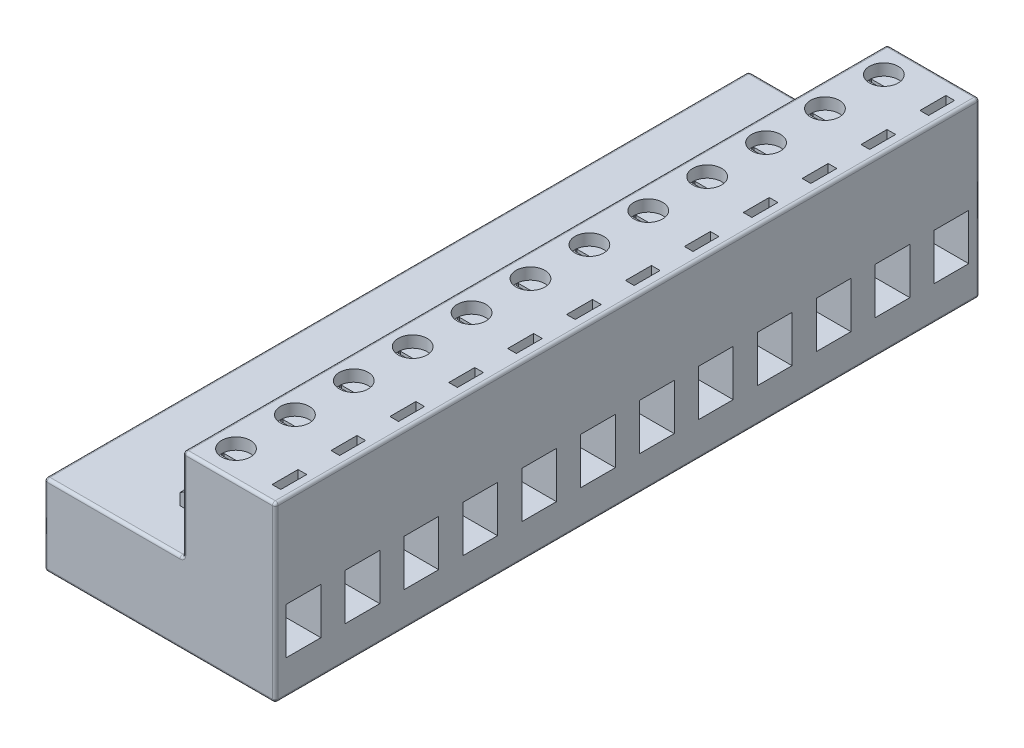
SolidWorks part; units mm, degrees
ref_plane "Front Plane" through (0, 0, 0) normal (0, 0, 1) x (1, 0, 0)
ref_plane "Top Plane" through (0, 0, 0) normal (0, 1, 0) x (1, 0, 0)
ref_plane "Right Plane" through (0, 0, 0) normal (1, 0, 0) x (0, 0, -1)
sketch "Sketch1" plane through (0, 0, 0) normal (0, 0, 1) x (1, 0, 0)
  line L0 (-4, -0.5) -> (-16, -0.5)
  line L1 (-4, -7.5) -> (4, -7.5)
  line L2 (-4, -7.5) -> (-4, 7.5)
  line L3 (-4, 7.5) -> (4, 7.5)
  line L4 (4, -7.5) -> (4, 7.5)
  line L5 (-4, -7.5) -> (4, 7.5) construction
  line L6 (-4, 7.5) -> (4, -7.5) construction
  line L7 (-16, -0.5) -> (-16, -7.5)
  line L8 (-16, -7.5) -> (-4, -7.5)
  point P0 (0, 0)
  dimension "D1" = 20
  dimension "D2" = 8
  dimension "D3" = 7
  dimension "D4" = 15
extrude "Boss-Extrude1" add sketch "Sketch1" along normal mid plane 61 contours L1 L4 L3 L2 | L7 L8 L2 L0
sketch "Sketch2" plane through (4, 0, 0) normal (1, 0, 0) x (0, 0, -1)
  line L0 (-30.5, -7.5) -> (30.5, -7.5) construction
  line L1 (-29.55, -0.5) -> (-26.55, -0.5)
  line L2 (-29.55, -0.5) -> (-29.55, -4.5)
  line L3 (-29.55, -4.5) -> (-26.55, -4.5)
  line L4 (-26.55, -0.5) -> (-26.55, -4.5)
  line L5 (-30.5, -7.5) -> (-30.5, 7.5) construction
  line L6 (-24.45, -0.5) -> (-24.45, -4.5)
  line L7 (-24.45, -0.5) -> (-21.45, -0.5)
  line L8 (-21.45, -0.5) -> (-21.45, -4.5)
  line L9 (-24.45, -4.5) -> (-21.45, -4.5)
  line L10 (-19.35, -0.5) -> (-19.35, -4.5)
  line L11 (-19.35, -0.5) -> (-16.35, -0.5)
  line L12 (-16.35, -0.5) -> (-16.35, -4.5)
  line L13 (-19.35, -4.5) -> (-16.35, -4.5)
  line L14 (-14.25, -0.5) -> (-14.25, -4.5)
  line L15 (-14.25, -0.5) -> (-11.25, -0.5)
  line L16 (-11.25, -0.5) -> (-11.25, -4.5)
  line L17 (-14.25, -4.5) -> (-11.25, -4.5)
  line L18 (-9.15, -0.5) -> (-9.15, -4.5)
  line L19 (-9.15, -0.5) -> (-6.15, -0.5)
  line L20 (-6.15, -0.5) -> (-6.15, -4.5)
  line L21 (-9.15, -4.5) -> (-6.15, -4.5)
  line L22 (-4.05, -0.5) -> (-4.05, -4.5)
  line L23 (-4.05, -0.5) -> (-1.05, -0.5)
  line L24 (-1.05, -0.5) -> (-1.05, -4.5)
  line L25 (-4.05, -4.5) -> (-1.05, -4.5)
  line L26 (1.05, -0.5) -> (1.05, -4.5)
  line L27 (1.05, -0.5) -> (4.05, -0.5)
  line L28 (4.05, -0.5) -> (4.05, -4.5)
  line L29 (1.05, -4.5) -> (4.05, -4.5)
  line L30 (6.15, -0.5) -> (6.15, -4.5)
  line L31 (6.15, -0.5) -> (9.15, -0.5)
  line L32 (9.15, -0.5) -> (9.15, -4.5)
  line L33 (6.15, -4.5) -> (9.15, -4.5)
  line L34 (11.25, -0.5) -> (11.25, -4.5)
  line L35 (11.25, -0.5) -> (14.25, -0.5)
  line L36 (14.25, -0.5) -> (14.25, -4.5)
  line L37 (11.25, -4.5) -> (14.25, -4.5)
  line L38 (16.35, -0.5) -> (16.35, -4.5)
  line L39 (16.35, -0.5) -> (19.35, -0.5)
  line L40 (19.35, -0.5) -> (19.35, -4.5)
  line L41 (16.35, -4.5) -> (19.35, -4.5)
  line L42 (21.45, -0.5) -> (21.45, -4.5)
  line L43 (21.45, -0.5) -> (24.45, -0.5)
  line L44 (24.45, -0.5) -> (24.45, -4.5)
  line L45 (21.45, -4.5) -> (24.45, -4.5)
  line L46 (26.55, -0.5) -> (26.55, -4.5)
  line L47 (26.55, -0.5) -> (29.55, -0.5)
  line L48 (29.55, -0.5) -> (29.55, -4.5)
  line L49 (26.55, -4.5) -> (29.55, -4.5)
  dimension "D1" = 3
  dimension "D2" = 4
  dimension "D3" = 3
  dimension "D4" = 0.95
  dimension "D5" = 12
extrude "Cut-Extrude1" cut sketch "Sketch2" against normal blind 6
sketch "Sketch3" plane through (0, 7.5, 0) normal (0, 1, 0) x (1, 0, 0)
  line L0 (-2, -28.05) -> (6.5761, -28.05) construction
  line L1 (-2, -26.55) -> (-2, -29.55) construction
  line L2 (-4, -30.5) -> (-4, 30.5) construction
  circle A0 centre (-1.85, -28.05) radius 1.25
  circle A1 centre (-1.85, -22.95) radius 1.25
  circle A2 centre (-1.85, -17.85) radius 1.25
  circle A3 centre (-1.85, -12.75) radius 1.25
  circle A4 centre (-1.85, -7.65) radius 1.25
  circle A5 centre (-1.85, -2.55) radius 1.25
  circle A6 centre (-1.85, 2.55) radius 1.25
  circle A7 centre (-1.85, 7.65) radius 1.25
  circle A8 centre (-1.85, 12.75) radius 1.25
  circle A9 centre (-1.85, 17.85) radius 1.25
  circle A10 centre (-1.85, 22.95) radius 1.25
  circle A11 centre (-1.85, 28.05) radius 1.25
  dimension "D1" = 2.15
  dimension "D3" = 2.5
  dimension "D2" = 12
extrude "Cut-Extrude2" cut sketch "Sketch3" against normal blind 1
sketch "Sketch4" plane through (0, 7.5, 0) normal (0, 1, 0) x (1, 0, 0)
  line L0 (-1.85, -28.05) -> (5.9871, -28.05) construction
  line L1 (2.4, -26.925) -> (3.15, -26.925)
  line L2 (2.4, -26.925) -> (2.4, -29.175)
  line L3 (2.4, -29.175) -> (3.15, -29.175)
  line L4 (3.15, -26.925) -> (3.15, -29.175)
  line L5 (4, -30.5) -> (4, 30.5) construction
  line L6 (2.4, -21.825) -> (2.4, -24.075)
  line L7 (2.4, -21.825) -> (3.15, -21.825)
  line L8 (3.15, -21.825) -> (3.15, -24.075)
  line L9 (2.4, -24.075) -> (3.15, -24.075)
  line L10 (2.4, -16.725) -> (2.4, -18.975)
  line L11 (2.4, -16.725) -> (3.15, -16.725)
  line L12 (3.15, -16.725) -> (3.15, -18.975)
  line L13 (2.4, -18.975) -> (3.15, -18.975)
  line L14 (2.4, -11.625) -> (2.4, -13.875)
  line L15 (2.4, -11.625) -> (3.15, -11.625)
  line L16 (3.15, -11.625) -> (3.15, -13.875)
  line L17 (2.4, -13.875) -> (3.15, -13.875)
  line L18 (2.4, -6.525) -> (2.4, -8.775)
  line L19 (2.4, -6.525) -> (3.15, -6.525)
  line L20 (3.15, -6.525) -> (3.15, -8.775)
  line L21 (2.4, -8.775) -> (3.15, -8.775)
  line L22 (2.4, -1.425) -> (2.4, -3.675)
  line L23 (2.4, -1.425) -> (3.15, -1.425)
  line L24 (3.15, -1.425) -> (3.15, -3.675)
  line L25 (2.4, -3.675) -> (3.15, -3.675)
  line L26 (2.4, 3.675) -> (2.4, 1.425)
  line L27 (2.4, 3.675) -> (3.15, 3.675)
  line L28 (3.15, 3.675) -> (3.15, 1.425)
  line L29 (2.4, 1.425) -> (3.15, 1.425)
  line L30 (2.4, 8.775) -> (2.4, 6.525)
  line L31 (2.4, 8.775) -> (3.15, 8.775)
  line L32 (3.15, 8.775) -> (3.15, 6.525)
  line L33 (2.4, 6.525) -> (3.15, 6.525)
  line L34 (2.4, 13.875) -> (2.4, 11.625)
  line L35 (2.4, 13.875) -> (3.15, 13.875)
  line L36 (3.15, 13.875) -> (3.15, 11.625)
  line L37 (2.4, 11.625) -> (3.15, 11.625)
  line L38 (2.4, 18.975) -> (2.4, 16.725)
  line L39 (2.4, 18.975) -> (3.15, 18.975)
  line L40 (3.15, 18.975) -> (3.15, 16.725)
  line L41 (2.4, 16.725) -> (3.15, 16.725)
  line L42 (2.4, 24.075) -> (2.4, 21.825)
  line L43 (2.4, 24.075) -> (3.15, 24.075)
  line L44 (3.15, 24.075) -> (3.15, 21.825)
  line L45 (2.4, 21.825) -> (3.15, 21.825)
  line L46 (2.4, 29.175) -> (2.4, 26.925)
  line L47 (2.4, 29.175) -> (3.15, 29.175)
  line L48 (3.15, 29.175) -> (3.15, 26.925)
  line L49 (2.4, 26.925) -> (3.15, 26.925)
  point P5 (2.4, -28.05)
  dimension "D1" = 2.25
  dimension "D2" = 0.75
  dimension "D3" = 0.85
  dimension "D4" = 12
extrude "Cut-Extrude3" cut sketch "Sketch4" against normal blind 2
sketch "Sketch5" plane through (-4, 0, 0) normal (-1, 0, 0) x (0, 0, 1)
  line L0 (30.5, -0.5) -> (-30.5, -0.5) construction
  line L1 (-26.75, 1.65) -> (-25.8, 1.65)
  line L2 (-26.75, 1.65) -> (-26.75, -0.5)
  line L3 (-26.75, -0.5) -> (-25.8, -0.5)
  line L4 (-25.8, 1.65) -> (-25.8, -0.5)
  line L5 (30.5, -0.5) -> (-30.5, -0.5) construction
  line L6 (-2.9788, 1.65) -> (-2.0288, 1.65)
  line L7 (-2.9788, 1.65) -> (-2.9788, -0.5)
  line L8 (-2.9788, -0.5) -> (-2.0288, -0.5)
  line L9 (-2.0288, 1.65) -> (-2.0288, -0.5)
  line L10 (-30.5, -0.5) -> (-30.5, 7.5) construction
  line L12 (0, -8.25) -> (0, 8.25) construction
  line L13 (2.0288, 1.65) -> (2.0288, -0.5)
  line L14 (2.9788, -0.5) -> (2.0288, -0.5)
  line L15 (2.9788, 1.65) -> (2.9788, -0.5)
  line L16 (2.9788, 1.65) -> (2.0288, 1.65)
  line L17 (25.8, 1.65) -> (25.8, -0.5)
  line L18 (26.75, -0.5) -> (25.8, -0.5)
  line L19 (26.75, 1.65) -> (26.75, -0.5)
  line L20 (26.75, 1.65) -> (25.8, 1.65)
  dimension "D1" = 3.75
  dimension "D2" = 0.95
  dimension "D3" = 2.15
extrude "Boss-Extrude2" add sketch "Sketch5" along normal blind 4
chamfer "Chamfer1" distance 2 angle 30 4 edges at (-8, 1.65, 26.275) (-8, 1.65, 2.5038) (-8, 1.65, -2.5038) (-8, 1.65, -26.275)
sketch "Sketch6" plane through (0, 6.5, 0) normal (0, 1, 0) x (1, 0, 0)
  line L0 (-0.675, -23.075) -> (-0.675, -22.825)
  line L1 (-0.675, -28.175) -> (-3.025, -28.175)
  line L2 (-0.675, -28.175) -> (-0.675, -27.925)
  line L3 (-0.675, -27.925) -> (-3.025, -27.925)
  line L4 (-3.025, -28.175) -> (-3.025, -27.925)
  line L5 (-0.675, -28.175) -> (-3.025, -27.925) construction
  line L6 (-0.675, -27.925) -> (-3.025, -28.175) construction
  line L7 (-0.675, -23.075) -> (-3.025, -23.075)
  line L8 (-3.025, -23.075) -> (-3.025, -22.825)
  line L9 (-0.675, -22.825) -> (-3.025, -22.825)
  line L10 (-0.675, -17.975) -> (-0.675, -17.725)
  line L11 (-0.675, -17.975) -> (-3.025, -17.975)
  line L12 (-3.025, -17.975) -> (-3.025, -17.725)
  line L13 (-0.675, -17.725) -> (-3.025, -17.725)
  line L14 (-0.675, -12.875) -> (-0.675, -12.625)
  line L15 (-0.675, -12.875) -> (-3.025, -12.875)
  line L16 (-3.025, -12.875) -> (-3.025, -12.625)
  line L17 (-0.675, -12.625) -> (-3.025, -12.625)
  line L18 (-0.675, -7.775) -> (-0.675, -7.525)
  line L19 (-0.675, -7.775) -> (-3.025, -7.775)
  line L20 (-3.025, -7.775) -> (-3.025, -7.525)
  line L21 (-0.675, -7.525) -> (-3.025, -7.525)
  line L22 (-0.675, -2.675) -> (-0.675, -2.425)
  line L23 (-0.675, -2.675) -> (-3.025, -2.675)
  line L24 (-3.025, -2.675) -> (-3.025, -2.425)
  line L25 (-0.675, -2.425) -> (-3.025, -2.425)
  line L26 (-0.675, 2.425) -> (-0.675, 2.675)
  line L27 (-0.675, 2.425) -> (-3.025, 2.425)
  line L28 (-3.025, 2.425) -> (-3.025, 2.675)
  line L29 (-0.675, 2.675) -> (-3.025, 2.675)
  line L30 (-0.675, 7.525) -> (-0.675, 7.775)
  line L31 (-0.675, 7.525) -> (-3.025, 7.525)
  line L32 (-3.025, 7.525) -> (-3.025, 7.775)
  line L33 (-0.675, 7.775) -> (-3.025, 7.775)
  line L34 (-0.675, 12.625) -> (-0.675, 12.875)
  line L35 (-0.675, 12.625) -> (-3.025, 12.625)
  line L36 (-3.025, 12.625) -> (-3.025, 12.875)
  line L37 (-0.675, 12.875) -> (-3.025, 12.875)
  line L38 (-0.675, 17.725) -> (-0.675, 17.975)
  line L39 (-0.675, 17.725) -> (-3.025, 17.725)
  line L40 (-3.025, 17.725) -> (-3.025, 17.975)
  line L41 (-0.675, 17.975) -> (-3.025, 17.975)
  line L42 (-0.675, 22.825) -> (-0.675, 23.075)
  line L43 (-0.675, 22.825) -> (-3.025, 22.825)
  line L44 (-3.025, 22.825) -> (-3.025, 23.075)
  line L45 (-0.675, 23.075) -> (-3.025, 23.075)
  line L46 (-0.675, 27.925) -> (-0.675, 28.175)
  line L47 (-0.675, 27.925) -> (-3.025, 27.925)
  line L48 (-3.025, 27.925) -> (-3.025, 28.175)
  line L49 (-0.675, 28.175) -> (-3.025, 28.175)
  point P0 (-1.85, -28.05)
  dimension "D1" = 0.25
  dimension "D2" = 2.35
  dimension "D3" = 12
extrude "Cut-Extrude4" cut sketch "Sketch6" against normal blind 0.25
fillet "Fillet1" radius 0.25 22 edges at (4, 0, -30.5) (0, 7.5, -30.5) (-4, 3.5, -30.5) (-10, -0.5, -30.5) (-6, -7.5, -30.5) (-10, -0.5, 30.5) (-4, 3.5, 30.5) (0, 7.5, 30.5) (4, 0, 30.5) (-6, -7.5, 30.5) (-16, -0.5, 0) (-16, -4, 30.5) (-16, -7.5, 0) (-16, -4, -30.5) (-4, -0.5, 28.625) (-4, -0.5, -28.625) (-4, -0.5, 0) (-4, -0.5, -14.3894) (-4, -0.5, 14.3894) (4, -7.5, 0) (4, 7.5, 0) (-4, 7.5, 0)
